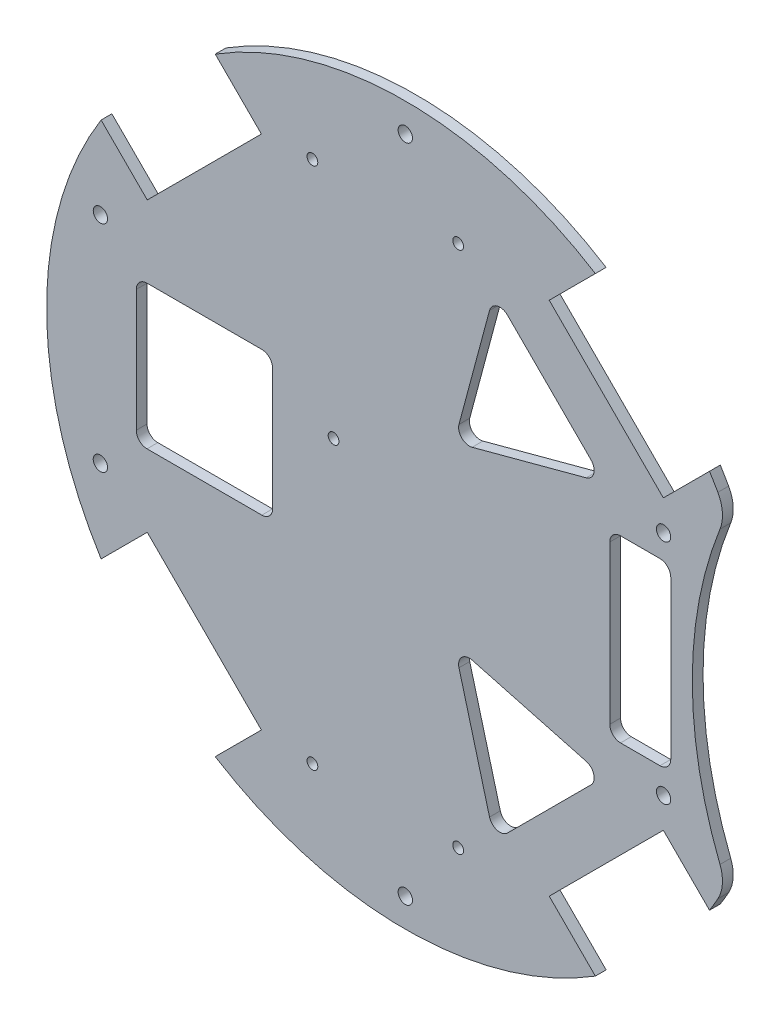
SolidWorks part; units mm, degrees
ref_plane "Alzado" through (0, 0, 0) normal (0, 0, 1) x (1, 0, 0)
ref_plane "Planta" through (0, 0, 0) normal (0, 1, 0) x (1, 0, 0)
ref_plane "Vista lateral" through (0, 0, 0) normal (1, 0, 0) x (0, 0, -1)
sketch "Croquis1" plane through (0, 0, 0) normal (0, 0, 1) x (1, 0, 0)
  circle A0 centre (0, 0) radius 100
  dimension "D1" = 200
extrude "Saliente-Extruir1" add sketch "Croquis1" along normal blind 3
sketch "Croquis3" plane through (0, 0, 3) normal (0, 0, 1) x (1, 0, 0)
  line L0 (0, 0) -> (190, 0) construction
  circle A0 centre (190, 0) radius 110
  dimension "D1" = 220
  dimension "D2" = 190
extrude "Cortar-Extruir1" cut sketch "Croquis3" against normal blind 3
fillet "Redondeo1" radius 10 2 edges at (89.4737, -44.6594, 1.5) (89.4737, 44.6594, 1.5)
sketch "Croquis7" plane through (0, 0, 3) normal (0, 0, 1) x (1, 0, 0)
  line L0 (-71.9393, -40.1195) -> (-40.1195, -71.9393)
  line L1 (-71.9393, -40.1195) -> (-89.617, -57.7972)
  line L2 (-40.1195, -71.9393) -> (-57.7972, -89.617)
  line L3 (-89.617, -57.7972) -> (-57.7972, -89.617)
  line L6 (0, -100) -> (0, 100) construction
  line L7 (-100, 0) -> (80, 0) construction
  line L8 (-40.1195, 71.9393) -> (-71.9393, 40.1195)
  line L9 (-40.1195, 71.9393) -> (-57.7972, 89.617)
  line L10 (-57.7972, 89.617) -> (-89.617, 57.7972)
  line L11 (-71.9393, 40.1195) -> (-89.617, 57.7972)
  line L12 (71.9393, 40.1195) -> (40.1195, 71.9393)
  line L13 (71.9393, 40.1195) -> (89.617, 57.7972)
  line L14 (89.617, 57.7972) -> (57.7972, 89.617)
  line L15 (40.1195, 71.9393) -> (57.7972, 89.617)
  line L16 (40.1195, -71.9393) -> (71.9393, -40.1195)
  line L17 (40.1195, -71.9393) -> (57.7972, -89.617)
  line L18 (57.7972, -89.617) -> (89.617, -57.7972)
  line L19 (71.9393, -40.1195) -> (89.617, -57.7972)
  line L20 (70.7107, -70.7107) -> (-70.7107, 70.7107) construction
  line L21 (-70.7107, -70.7107) -> (70.7107, 70.7107) construction
  arc A0 (87.1345, 49.0671) -> (87.1345, -49.0671) centre (0, 0) ccw construction
  arc A1 (87.1345, 49.0671) -> (87.1345, -49.0671) centre (0, 0) ccw construction
  arc A4 (87.7193, 40.4803) -> (87.7193, -40.4803) centre (190, 0) ccw construction
  point P24 (0, 0)
  dimension "D1" = 22.5
  dimension "D2" = 45
  dimension "D3" = 25
  dimension "D4" = 45
  dimension "D5" = 200
  dimension "D6" = 4
  dimension "D7" = 79.2376
  dimension "D8" = 22.5
  dimension "D9" = 200
  dimension "D10" = 45
  dimension "D11" = 90
  dimension "D12" = 79.2376
extrude "Cortar-Extruir3" cut sketch "Croquis7" against normal blind 10
sketch "Croquis10" plane through (0, 0, 3) normal (0, 0, 1) x (1, 0, 0)
  line L0 (80, 0) -> (-100, 0) construction
  circle A0 centre (-20, 8.5) radius 1.5
  arc A1 (-84.8075, 52.9877) -> (-84.8075, -52.9877) centre (0, 0) ccw construction
  circle A2 centre (14.74, 72.95) radius 1.5
  circle A3 centre (-25.9, 72.95) radius 1.5
  arc A4 (52.9877, 84.8075) -> (-52.9877, 84.8075) centre (0, 0) ccw construction
  arc A5 (87.7193, 40.4803) -> (87.7193, -40.4803) centre (190, 0) ccw construction
  circle A6 centre (14.74, -72.95) radius 1.5
  circle A7 centre (-25.9, -72.95) radius 1.5
  dimension "D1" = 3
  dimension "D2" = 8.5
  dimension "D3" = 20
  dimension "D4" = 3
  dimension "D5" = 3
  dimension "D6" = 40.64
  dimension "D7" = 72.95
  dimension "D8" = 25.9
  dimension "D9" = 72.95
extrude "Cortar-Extruir4" cut sketch "Croquis10" against normal through all
sketch "Croquis11" plane through (0, 0, 3) normal (0, 0, 1) x (1, 0, 0)
  line L0 (-100, 0) -> (80, 0) construction
  line L5 (0, 0) -> (0, 100) construction
  line L6 (74, 25) -> (57, 25)
  line L7 (74, 25) -> (74, -25)
  line L8 (74, -25) -> (57, -25)
  line L9 (57, 25) -> (57, -25)
  line L10 (55.4435, 35.5616) -> (24.8249, 66.1802)
  line L11 (24.8249, 66.1802) -> (13.6177, 24.3544)
  line L12 (13.6177, 24.3544) -> (55.4435, 35.5616)
  line L13 (13.6177, -24.3544) -> (55.4435, -35.5616)
  line L14 (24.8249, -66.1802) -> (13.6177, -24.3544)
  line L15 (55.4435, -35.5616) -> (24.8249, -66.1802)
  line L16 (71.9393, 40.1195) -> (84.8075, 52.9877) construction
  line L17 (-52.9877, -84.8075) -> (-40.1195, -71.9393) construction
  line L19 (-37, 20) -> (-75, 20)
  line L20 (-37, 20) -> (-37, -20)
  line L21 (-37, -20) -> (-75, -20)
  line L22 (-75, 20) -> (-75, -20)
  arc A0 (-84.8075, 52.9877) -> (-84.8075, -52.9877) centre (0, 0) ccw construction
  arc A1 (87.7193, 40.4803) -> (87.7193, -40.4803) centre (190, 0) ccw construction
  circle A2 centre (31.2953, 42.032) radius 12.5 construction
  arc A3 (52.9877, 84.8075) -> (-52.9877, 84.8075) centre (0, 0) ccw construction
  circle A4 centre (0, 92) radius 2
  circle A7 centre (0, -92) radius 2
  arc A10 (-52.9877, -84.8075) -> (52.9877, -84.8075) centre (0, 0) ccw construction
  arc A13 (-84.8075, 52.9877) -> (-84.8075, -52.9877) centre (0, 0) ccw construction
  circle A15 centre (72, 31.6949) radius 2
  circle A16 centre (72, -31.6949) radius 2
  circle A17 centre (-85, -30) radius 2
  circle A18 centre (-85, 30) radius 2
  point P45 (0, 0)
  dimension "D9" = 25
  dimension "D12" = 15
  dimension "D13" = 4
  dimension "D14" = 92
  dimension "D15" = 4
  dimension "D16" = 92
  dimension "D17" = 42.5538
  dimension "D18" = 4
  dimension "D19" = 6
  dimension "D20" = 72
  dimension "D21" = 4
  dimension "D22" = 30
  dimension "D23" = 85
  dimension "D24" = 4
  dimension "D25" = 30
  dimension "D26" = 85
  dimension "D27" = 38
  dimension "D28" = 75
  dimension "D3" = 20
  dimension "D4" = 20
  dimension "D5" = 25
  dimension "D6" = 50
  dimension "D7" = 57
  dimension "D8" = 17
  dimension "D10" = 20
  dimension "D11" = 70
extrude "Cortar-Extruir5" cut sketch "Croquis11" against normal blind 10
fillet "Redondeo2" radius 3 14 edges at (13.6177, -24.3544, 1.5) (24.8249, -66.1802, 1.5) (55.4435, -35.5616, 1.5) (74, -25, 1.5) (57, -25, 1.5) (74, 25, 1.5) (57, 25, 1.5) (55.4435, 35.5616, 1.5) (13.6177, 24.3544, 1.5) (24.8249, 66.1802, 1.5) (-75, -20, 1.5) (-37, -20, 1.5) (-75, 20, 1.5) (-37, 20, 1.5)
